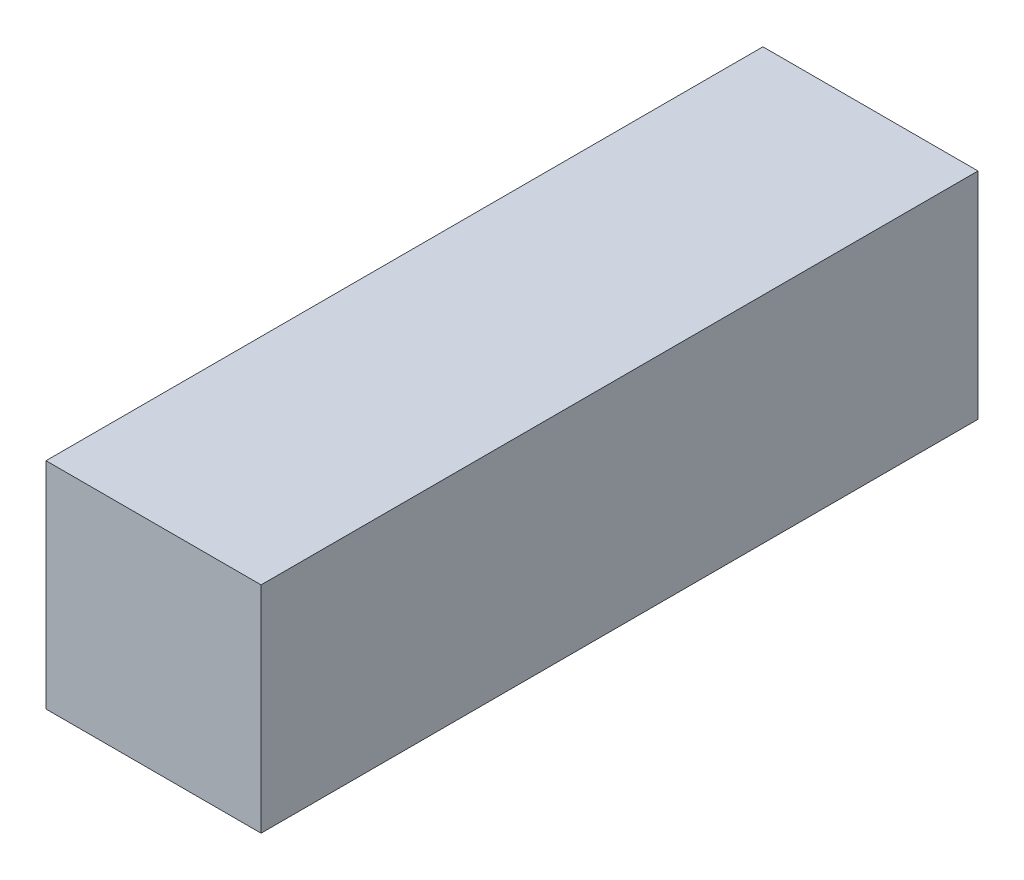
SolidWorks part; units mm, degrees
material "AISI 1045 Steel, cold drawn"
ref_plane "Front Plane" through (0, 0, 0) normal (0, 0, 1) x (1, 0, 0)
ref_plane "Top Plane" through (0, 0, 0) normal (0, 1, 0) x (1, 0, 0)
ref_plane "Right Plane" through (0, 0, 0) normal (1, 0, 0) x (0, 0, -1)
sketch "Sketch1" plane through (0, 0, 0) normal (0, 0, 1) x (1, 0, 0)
  line L1 (-3, 13.4) -> (3, 13.4)
  line L2 (-3, 13.4) -> (-3, 7.4)
  line L3 (-3, 7.4) -> (3, 7.4)
  line L4 (3, 13.4) -> (3, 7.4)
  dimension "D1" = 6
  dimension "D2" = 3
  dimension "D3" = 13.4
  dimension "D4" = 3
extrude "Boss-Extrude1" add sketch "Sketch1" along normal blind 20
